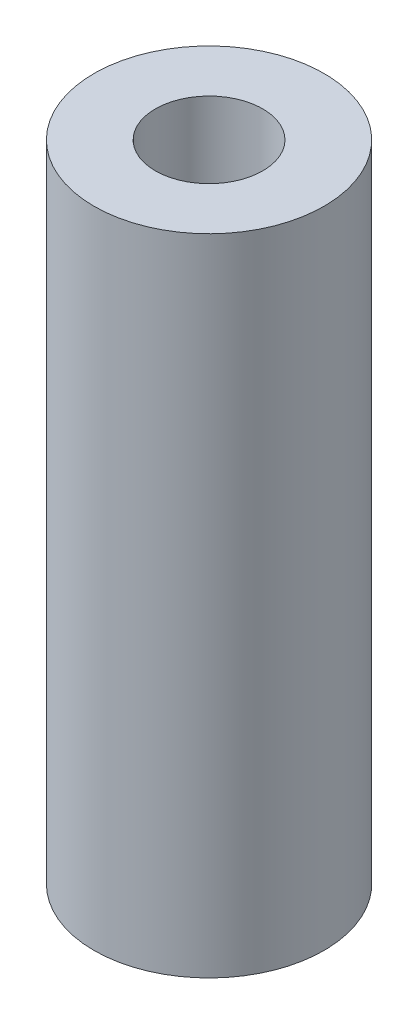
SolidWorks part; units mm, degrees
material "Ceramic Porcelain"
ref_plane "Front Plane" through (0, 0, 0) normal (0, 0, 1) x (1, 0, 0)
ref_plane "Top Plane" through (0, 0, 0) normal (0, 1, 0) x (1, 0, 0)
ref_plane "Right Plane" through (0, 0, 0) normal (1, 0, 0) x (0, 0, -1)
sketch "Sketch1" plane through (0, 0, 0) normal (0, 1, 0) x (1, 0, 0)
  circle A0 centre (0, 0) radius 3.2639
  circle A1 centre (0, 0) radius 1.524
  dimension "D1" = 6.5278
  dimension "D2" = 3.048
extrude "Boss-Extrude1" add sketch "Sketch1" along normal blind 18.288
